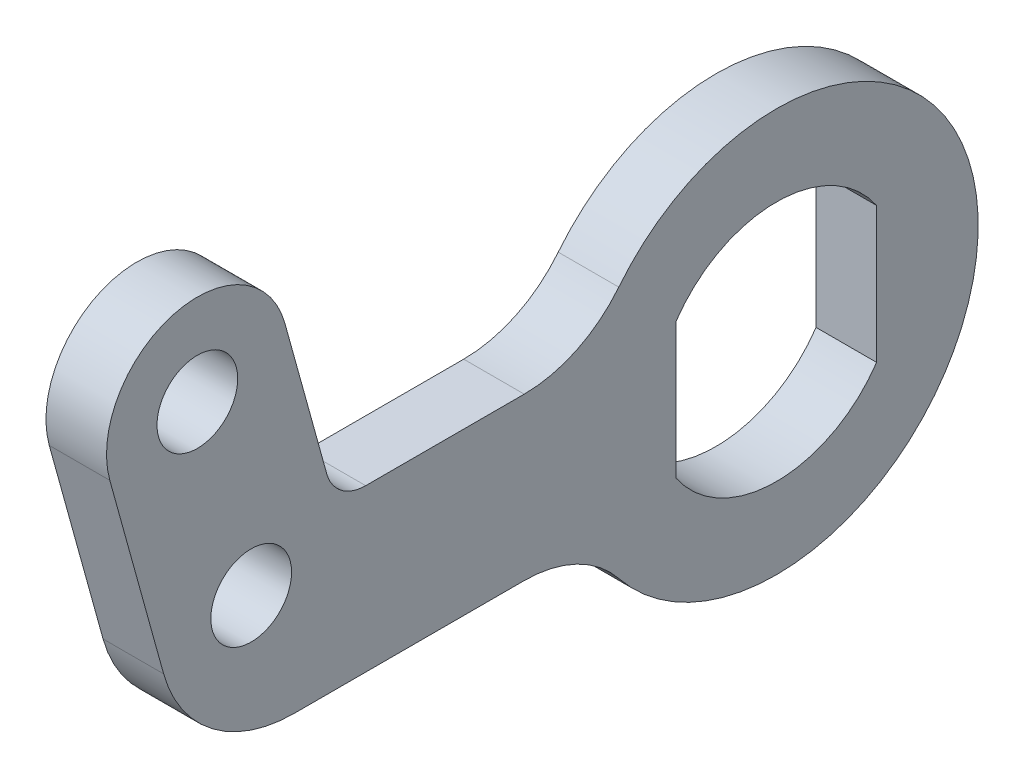
SolidWorks part; units mm, degrees
ref_plane "Front Plane" through (0, 0, 0) normal (0, 0, 1) x (1, 0, 0)
ref_plane "Top Plane" through (0, 0, 0) normal (0, 1, 0) x (1, 0, 0)
ref_plane "Right Plane" through (0, 0, 0) normal (1, 0, 0) x (0, 0, -1)
sketch "Sketch1" plane through (0, 0, 0) normal (1, 0, 0) x (0, 0, -1)
  line L0 (0, 0) -> (13.0091, 0) construction
  line L1 (13.0091, 0) -> (15.4924, 0) construction
  line L2 (13.0091, 0) -> (10.5258, 0) construction
  line L3 (10.5258, 1.6832) -> (10.5258, -1.6832)
  line L4 (15.4924, 1.6832) -> (15.4924, -1.6832)
  line L5 (13.0091, 0) -> (9.106, 0) construction
  line L6 (9.106, 3.125) -> (9.106, -3.125) construction
  line L7 (6.7641, 2) -> (2.8366, 2)
  line L8 (6.7641, -2) -> (1.0704, -2)
  line L9 (-2.1685, 0.4644) -> (-3.5019, 5.2834)
  line L10 (1.8728, 2.7333) -> (0.8351, 6.4834)
  line L11 (0, 0) -> (0, 1.0645) construction
  circle A0 centre (13.0091, 0) radius 5 construction
  circle A1 centre (13.0091, 0) radius 3 construction
  arc A2 (10.5258, 1.6832) -> (15.4924, 1.6832) centre (13.0091, 0) cw
  arc A3 (10.5258, -1.6832) -> (15.4924, -1.6832) centre (13.0091, 0) ccw
  arc A4 (9.106, 3.125) -> (9.106, -3.125) centre (13.0091, 0) cw
  arc A5 (9.106, 3.125) -> (6.7641, 2) centre (6.7641, 5) cw
  arc A6 (9.106, -3.125) -> (6.7641, -2) centre (6.7641, -5) ccw
  arc A7 (2.8366, 2) -> (1.8728, 2.7333) centre (2.8366, 3) cw
  arc A8 (1.0704, -2) -> (-2.1685, 0.4644) centre (1.0704, 1.3606) cw
  arc A9 (-3.5019, 5.2834) -> (0.8351, 6.4834) centre (-1.3334, 5.8834) cw
  circle A12 centre (-1.3334, 5.8834) radius 1
  circle A14 centre (0, 1.0645) radius 1
  dimension "D1" = 10
  dimension "D3" = 2.4833
  dimension "D4" = 3.9031
  dimension "D5" = 3
  dimension "D6" = 3.9275
  dimension "D7" = 1
  dimension "D8" = 3.3606
  dimension "D10" = 2.25
  dimension "D11" = 5.6937
  dimension "D12" = 5
  dimension "D13" = 3.891
  dimension "D14" = 3
  dimension "D15" = 2
  dimension "D16" = 2
  dimension "D2" = 13.0091
  dimension "D9" = 1.0645
extrude "Boss-Extrude3" add sketch "Sketch1" along normal blind 1.5
